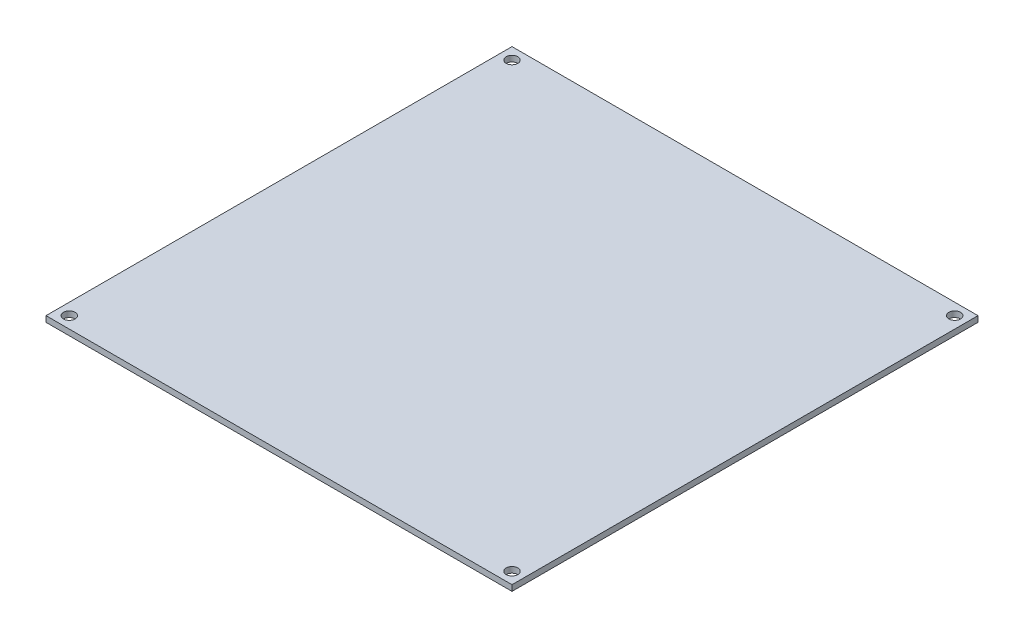
SolidWorks part; units mm, degrees
ref_plane "Front Plane" through (0, 0, 0) normal (0, 0, 1) x (1, 0, 0)
ref_plane "Top Plane" through (0, 0, 0) normal (0, 1, 0) x (1, 0, 0)
ref_plane "Right Plane" through (0, 0, 0) normal (1, 0, 0) x (0, 0, -1)
sketch "Sketch1" plane through (0, 0, 0) normal (0, 1, 0) x (1, 0, 0)
  line L1 (0, 0) -> (127, 0)
  line L2 (0, 0) -> (0, 127)
  line L3 (0, 127) -> (127, 127)
  line L4 (127, 0) -> (127, 127)
  circle A0 centre (3.175, 123.825) radius 1.5875
  circle A1 centre (123.825, 123.825) radius 1.5875
  circle A2 centre (123.825, 3.175) radius 1.5875
  circle A3 centre (3.175, 3.175) radius 1.5875
  point P13 (0, 0)
  point P14 (0, 0)
  point P15 (0, 0)
  point P16 (0, 0)
  dimension "D3" = 3.175
  dimension "D1" = 127
  dimension "D2" = 127
  dimension "D4" = 3.175
  dimension "D5" = 3.175
  dimension "D6" = 3.175
  dimension "D7" = 3.175
extrude "Boss-Extrude1" add sketch "Sketch1" along normal blind 1.5875
